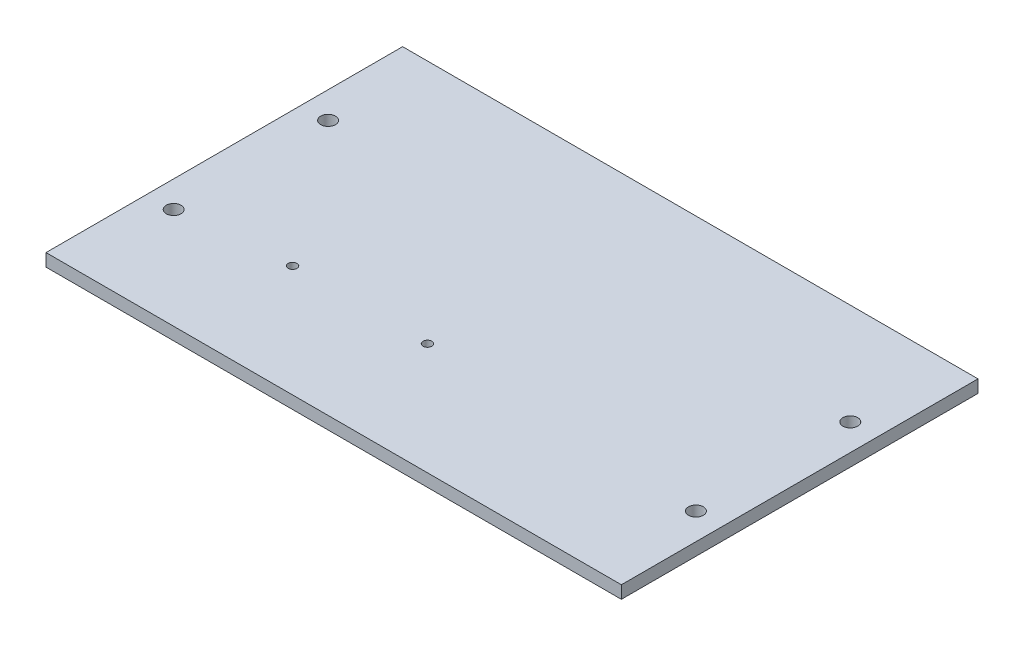
SolidWorks part; units mm, degrees
material "Acrylic (Medium-high impact)"
ref_plane "Front Plane" through (0, 0, 0) normal (0, 0, 1) x (1, 0, 0)
ref_plane "Top Plane" through (0, 0, 0) normal (0, 1, 0) x (1, 0, 0)
ref_plane "Right Plane" through (0, 0, 0) normal (1, 0, 0) x (0, 0, -1)
sketch "Sketch1" plane through (0, 0, 0) normal (0, 1, 0) x (1, 0, 0)
  line L1 (0, 0) -> (216.7839, 0)
  line L2 (0, 0) -> (0, 134.366)
  line L3 (0, 134.366) -> (216.7839, 134.366)
  line L4 (216.7839, 0) -> (216.7839, 134.366)
  circle A0 centre (50.8, 42.1007) radius 1.651
  circle A1 centre (101.6, 42.1007) radius 1.651
  circle A2 centre (10.0076, 96.266) radius 2.794
  circle A3 centre (10.0076, 38.1) radius 2.794
  circle A4 centre (206.7763, 96.266) radius 2.794
  circle A5 centre (206.7763, 38.1) radius 2.794
  dimension "D3" = 3.302
  dimension "D4" = 3.302
  dimension "D7" = 5.588
  dimension "D8" = 5.588
  dimension "D9" = 5.588
  dimension "D10" = 5.588
  dimension "D1" = 134.366
  dimension "D2" = 216.7839
  dimension "D5" = 50.8
  dimension "D6" = 50.8
  dimension "D11" = 10.0076
  dimension "D12" = 10.0076
  dimension "D13" = 38.1
  dimension "D14" = 38.1
  dimension "D15" = 38.1
  dimension "D16" = 38.1
  dimension "D17" = 10.0076
  dimension "D18" = 10.0076
extrude "Boss-Extrude1" add sketch "Sketch1" along normal blind 4.7625
